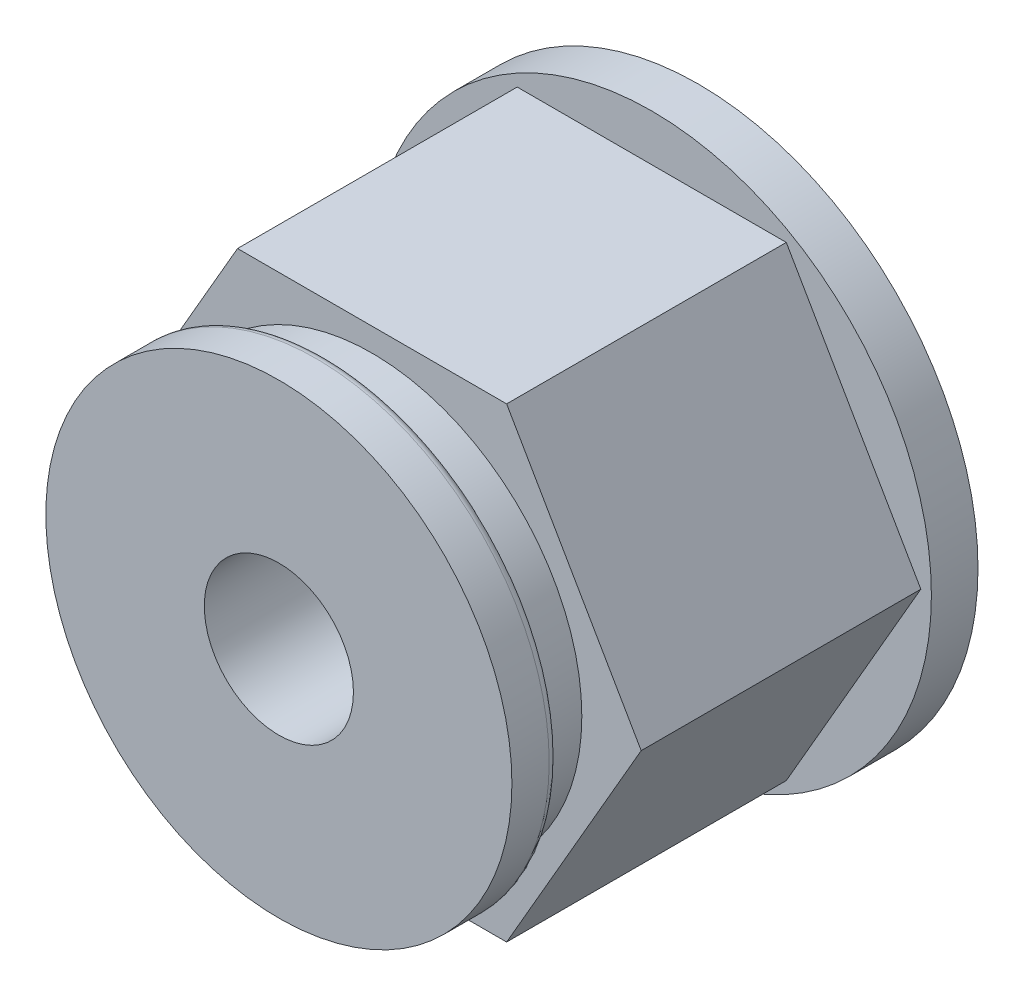
SolidWorks part; units mm, degrees
ref_plane "Front Plane" through (0, 0, 0) normal (0, 0, 1) x (1, 0, 0)
ref_plane "Top Plane" through (0, 0, 0) normal (0, 1, 0) x (1, 0, 0)
ref_plane "Right Plane" through (0, 0, 0) normal (1, 0, 0) x (0, 0, -1)
sketch "Sketch1" plane through (0, 0, 0) normal (0, 0, 1) x (1, 0, 0)
  circle A0 centre (0, 0) radius 7.62
  dimension "D1" = 15.24
extrude "Boss-Extrude1" add sketch "Sketch1" along normal blind 1.27
sketch "Sketch2" plane through (0, 0, 1.27) normal (0, 0, 1) x (1, 0, 0)
  line L1 (3.6662, 6.35) -> (-3.6662, 6.35)
  line L2 (-3.6662, 6.35) -> (-7.3323, 0)
  line L3 (-7.3323, 0) -> (-3.6662, -6.35)
  line L4 (-3.6662, -6.35) -> (3.6662, -6.35)
  line L5 (3.6662, -6.35) -> (7.3323, 0)
  line L6 (7.3323, 0) -> (3.6662, 6.35)
  circle A0 centre (0, 0) radius 6.35 construction
  point P1 (0, -6.35)
  dimension "D1" = 12.7
extrude "Boss-Extrude2" add sketch "Sketch2" along normal blind 7.62
sketch "Sketch3" plane through (0, 0, 8.89) normal (0, 0, 1) x (1, 0, 0)
  circle A0 centre (0, 0) radius 5.715
  dimension "D1" = 11.43
extrude "Boss-Extrude3" add sketch "Sketch3" along normal blind 1.27 contours A0
sketch "Sketch4" plane through (0, 0, 10.16) normal (0, 0, 1) x (1, 0, 0)
  circle A0 centre (0, 0) radius 6.35
  dimension "D1" = 12.7
extrude "Boss-Extrude4" add sketch "Sketch4" along normal blind 1.27 contours A0
fillet "Fillet1" radius 0.254 2 edges at (6.35, 0, 10.16) (5.715, 0, 10.16)
sketch "Sketch5" plane through (0, 0, 11.43) normal (0, 0, 1) x (1, 0, 0)
  circle A0 centre (0, 0) radius 2.032
  dimension "D1" = 4.064
extrude "Cut-Extrude1" cut sketch "Sketch5" against normal up to surface (11.43 mm away) up to face at (7.62, 0, 0)
